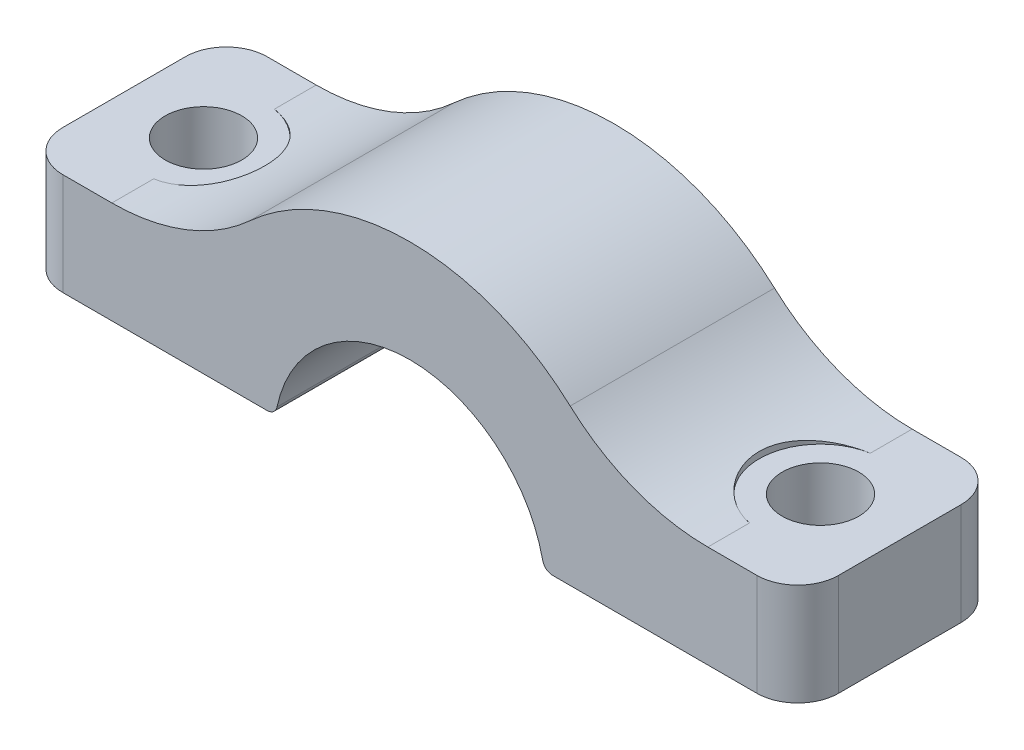
SolidWorks part; units mm, degrees
ref_plane "Front Plane" through (0, 0, 0) normal (0, 0, 1) x (1, 0, 0)
ref_plane "Top Plane" through (0, 0, 0) normal (0, 1, 0) x (1, 0, 0)
ref_plane "Right Plane" through (0, 0, 0) normal (1, 0, 0) x (0, 0, -1)
sketch "Sketch1" plane through (0, 0, 0) normal (0, 0, 1) x (1, 0, 0)
  line L0 (-18.9861, 1) -> (-6.5744, 1)
  line L1 (6.5744, 1) -> (18.9861, 1)
  line L2 (18.9861, 1) -> (18.9861, 6)
  line L3 (18.9861, 6) -> (9.9861, 6)
  line L4 (-9.9861, 6) -> (-18.9861, 6)
  line L5 (-18.9861, 6) -> (-18.9861, 1)
  line L6 (0, -5.5) -> (0, 5.5) construction
  arc A0 (-6.5744, 1) -> (6.5744, 1) centre (0, 0) cw
  arc A2 (-9.9861, 6) -> (9.9861, 6) centre (0, 0) cw
  dimension "D2" = 6.65
  dimension "D1" = 5
  dimension "D3" = 5
  dimension "D4" = 9
  dimension "D5" = 9
  dimension "D6" = 1
extrude "Boss-Extrude1" add sketch "Sketch1" along normal blind 10
fillet "Fillet1" radius 2 4 edges at (18.9861, 3.5, 0) (-18.9861, 3.5, 0) (18.9861, 3.5, 10) (-18.9861, 3.5, 10)
fillet "Fillet3" radius 0.5 2 edges at (-6.5744, 1, 5) (6.5744, 1, 5)
fillet "Fillet4" radius 10 2 edges at (9.9861, 6, 5) (-9.9861, 6, 5)
sketch "Sketch2" plane through (0, 0, 0) normal (0, 1, 0) x (1, 0, 0)
  line L1 (-12.815, 0) -> (12.815, 0) construction
  line L2 (0, -5.5) -> (0, 5.5) construction
  circle A0 centre (-15.1, -5) radius 1.875
  circle A1 centre (15.1, -5) radius 1.875
  point P2 (-15.504, -4.6877)
  point P5 (0, 0)
  point P7 (-15.504, -5)
  dimension "D1" = 3.75
  dimension "D2" = 5
  dimension "D3" = 15.1
extrude "Cut-Extrude1" cut sketch "Sketch2" along normal through all
sketch "Sketch3" plane through (0, 0, 0) normal (0, 1, 0) x (1, 0, 0)
  line L0 (0, -5.5) -> (0, 5.5) construction
  circle A0 centre (-15.1, -5) radius 3
  circle A1 centre (15.1, -5) radius 3
  dimension "D1" = 6
extrude "Cut-Extrude2" cut sketch "Sketch3" along normal blind 10 from offset 6
equation "\"shaftDiameter\"= 12.7mm"
equation "\"D2@Sketch1\"=\"shaftDiameter\"/2 +0.3"
equation "\"holeDiameter\"= 3.75mm"
equation "\"D1@Sketch2\"=3.75"
